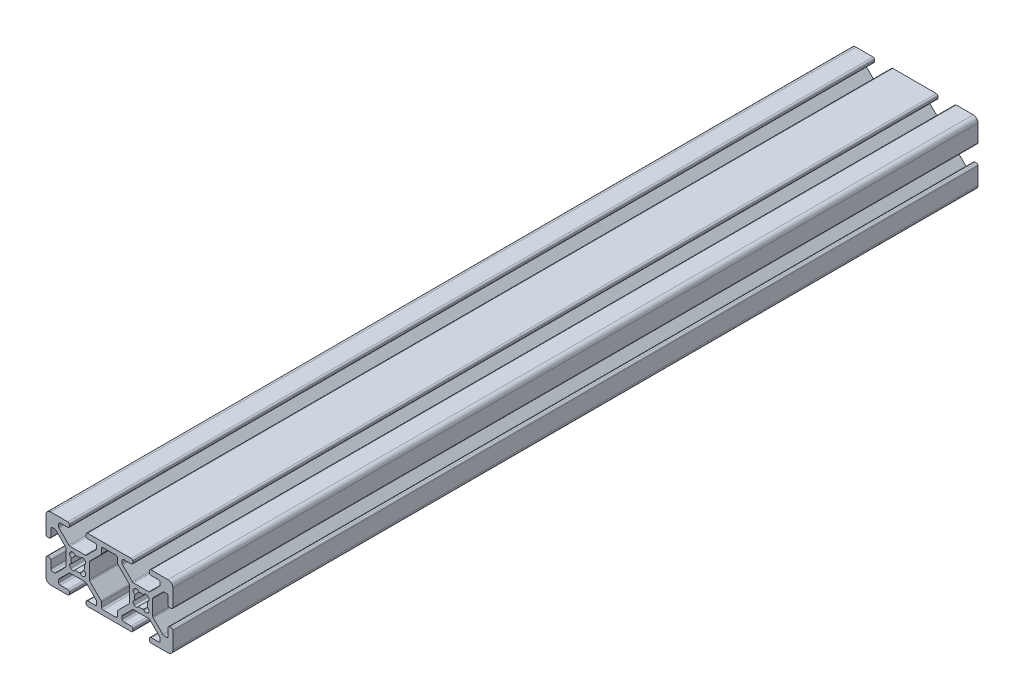
SolidWorks part; units mm, degrees
ref_plane "Front Plane" through (0, 0, 0) normal (0, 0, 1) x (1, 0, 0)
ref_plane "Top Plane" through (0, 0, 0) normal (0, 1, 0) x (1, 0, 0)
ref_plane "Right Plane" through (0, 0, 0) normal (1, 0, 0) x (0, 0, -1)
sketch "Sketch1" plane through (0, 0, 0) normal (0, 0, 1) x (1, 0, 0)
  line L0 (-16.6492, -61.9845) -> (-16.8288, -61.8049)
  line L1 (-16.8288, -57.5551) -> (-16.6492, -57.3755)
  line L2 (-12.3994, -57.3755) -> (-12.2198, -57.5551)
  line L3 (-12.2198, -61.8049) -> (-12.3994, -61.9845)
  line L4 (-27.0293, -67.672) -> (-27.0293, -66.3248)
  line L5 (-27.1781, -65.9655) -> (-30.7205, -62.4231)
  line L6 (-30.8693, -62.0639) -> (-30.8693, -57.2961)
  line L7 (-30.7205, -56.9369) -> (-27.1781, -53.3944)
  line L8 (-27.0293, -53.0352) -> (-27.0293, -51.688)
  line L9 (-26.5213, -51.18) -> (-22.5273, -51.18)
  line L10 (-22.0193, -51.688) -> (-22.0193, -53.0352)
  line L11 (-21.8705, -53.3944) -> (-18.3281, -56.9369)
  line L12 (-18.1793, -57.2961) -> (-18.1793, -62.0639)
  line L13 (-18.3281, -62.4231) -> (-21.8705, -65.9655)
  line L14 (-22.0193, -66.3248) -> (-22.0193, -67.672)
  line L15 (-22.5273, -68.18) -> (-26.5213, -68.18)
  line L16 (-36.6492, -61.9845) -> (-36.8288, -61.8049)
  line L17 (-36.8288, -57.5551) -> (-36.6492, -57.3755)
  line L18 (-32.3994, -57.3755) -> (-32.2198, -57.5551)
  line L19 (-32.2198, -61.8049) -> (-32.3994, -61.9845)
  line L20 (-36.9082, -63.335) -> (-32.1404, -63.335)
  line L21 (-31.7812, -63.4838) -> (-28.6781, -66.5869)
  line L22 (-28.5293, -66.9461) -> (-28.5293, -67.672)
  line L23 (-29.0373, -68.18) -> (-31.3863, -68.18)
  line L24 (-31.8943, -68.688) -> (-31.8943, -69.172)
  line L25 (-31.3863, -69.68) -> (-17.6623, -69.68)
  line L26 (-17.1543, -69.172) -> (-17.1543, -68.688)
  line L27 (-17.6623, -68.18) -> (-20.0113, -68.18)
  line L28 (-20.5193, -67.672) -> (-20.5193, -66.9461)
  line L29 (-20.3705, -66.5869) -> (-17.2674, -63.4838)
  line L30 (-16.9082, -63.335) -> (-12.1404, -63.335)
  line L31 (-11.7812, -63.4838) -> (-8.6781, -66.5869)
  line L32 (-8.5293, -66.9461) -> (-8.5293, -67.672)
  line L33 (-9.0373, -68.18) -> (-11.3863, -68.18)
  line L34 (-11.8943, -68.688) -> (-11.8943, -69.172)
  line L35 (-11.3863, -69.68) -> (-6.0243, -69.68)
  line L36 (-4.5243, -68.18) -> (-4.5243, -62.818)
  line L37 (-5.0323, -62.31) -> (-5.5163, -62.31)
  line L38 (-6.0243, -62.818) -> (-6.0243, -65.167)
  line L39 (-6.5323, -65.675) -> (-7.2582, -65.675)
  line L40 (-7.6174, -65.5262) -> (-10.7205, -62.4231)
  line L41 (-10.8693, -62.0639) -> (-10.8693, -57.2961)
  line L42 (-10.7205, -56.9369) -> (-7.6174, -53.8338)
  line L43 (-7.2582, -53.685) -> (-6.5323, -53.685)
  line L44 (-6.0243, -54.193) -> (-6.0243, -56.542)
  line L45 (-5.5163, -57.05) -> (-5.0323, -57.05)
  line L46 (-4.5243, -56.542) -> (-4.5243, -51.18)
  line L47 (-6.0243, -49.68) -> (-11.3863, -49.68)
  line L48 (-11.8943, -50.188) -> (-11.8943, -50.672)
  line L49 (-11.3863, -51.18) -> (-9.0373, -51.18)
  line L50 (-8.5293, -51.688) -> (-8.5293, -52.4139)
  line L51 (-8.6781, -52.7731) -> (-11.7812, -55.8762)
  line L52 (-12.1404, -56.025) -> (-16.9082, -56.025)
  line L53 (-17.2674, -55.8762) -> (-20.3705, -52.7731)
  line L54 (-20.5193, -52.4139) -> (-20.5193, -51.688)
  line L55 (-20.0113, -51.18) -> (-17.6623, -51.18)
  line L56 (-17.1543, -50.672) -> (-17.1543, -50.188)
  line L57 (-17.6623, -49.68) -> (-31.3863, -49.68)
  line L58 (-31.8943, -50.188) -> (-31.8943, -50.672)
  line L59 (-31.3863, -51.18) -> (-29.0373, -51.18)
  line L60 (-28.5293, -51.688) -> (-28.5293, -52.4139)
  line L61 (-28.6781, -52.7731) -> (-31.7812, -55.8762)
  line L62 (-32.1404, -56.025) -> (-36.9082, -56.025)
  line L63 (-37.2674, -55.8762) -> (-40.3705, -52.7731)
  line L64 (-40.5193, -52.4139) -> (-40.5193, -51.688)
  line L65 (-40.0113, -51.18) -> (-37.6623, -51.18)
  line L66 (-37.1543, -50.672) -> (-37.1543, -50.188)
  line L67 (-37.6623, -49.68) -> (-43.0243, -49.68)
  line L68 (-44.5243, -51.18) -> (-44.5243, -56.542)
  line L69 (-44.0163, -57.05) -> (-43.5323, -57.05)
  line L70 (-43.0243, -56.542) -> (-43.0243, -54.193)
  line L71 (-42.5163, -53.685) -> (-41.7904, -53.685)
  line L72 (-41.4312, -53.8338) -> (-38.3281, -56.9369)
  line L73 (-38.1793, -57.2961) -> (-38.1793, -62.0639)
  line L74 (-38.3281, -62.4231) -> (-41.4312, -65.5262)
  line L75 (-41.7904, -65.675) -> (-42.5163, -65.675)
  line L76 (-43.0243, -65.167) -> (-43.0243, -62.818)
  line L77 (-43.5323, -62.31) -> (-44.0163, -62.31)
  line L78 (-44.5243, -62.818) -> (-44.5243, -68.18)
  line L79 (-43.0243, -69.68) -> (-37.6623, -69.68)
  line L80 (-37.1543, -69.172) -> (-37.1543, -68.688)
  line L81 (-37.6623, -68.18) -> (-40.0113, -68.18)
  line L82 (-40.5193, -67.672) -> (-40.5193, -66.9461)
  line L83 (-40.3705, -66.5869) -> (-37.2674, -63.4838)
  arc A0 (-16.4594, -60.484) -> (-16.8288, -61.8049) centre (-16.2723, -61.2484) ccw
  arc A1 (-16.4594, -58.876) -> (-16.4594, -60.484) centre (-14.5243, -59.68) ccw
  arc A2 (-16.8288, -57.5551) -> (-16.4594, -58.876) centre (-16.2723, -58.1116) ccw
  arc A3 (-15.3283, -57.7449) -> (-16.6492, -57.3755) centre (-16.0927, -57.932) ccw
  arc A4 (-13.7203, -57.7449) -> (-15.3283, -57.7449) centre (-14.5243, -59.68) ccw
  arc A5 (-12.3994, -57.3755) -> (-13.7203, -57.7449) centre (-12.9559, -57.932) ccw
  arc A6 (-12.5892, -58.876) -> (-12.2198, -57.5551) centre (-12.7763, -58.1116) ccw
  arc A7 (-12.5892, -60.484) -> (-12.5892, -58.876) centre (-14.5243, -59.68) ccw
  arc A8 (-12.2198, -61.8049) -> (-12.5892, -60.484) centre (-12.7763, -61.2484) ccw
  arc A9 (-13.7203, -61.6151) -> (-12.3994, -61.9845) centre (-12.9559, -61.428) ccw
  arc A10 (-15.3283, -61.6151) -> (-13.7203, -61.6151) centre (-14.5243, -59.68) ccw
  arc A11 (-16.6492, -61.9845) -> (-15.3283, -61.6151) centre (-16.0927, -61.428) ccw
  arc A12 (-27.0293, -67.672) -> (-26.5213, -68.18) centre (-26.5213, -67.672) ccw
  arc A13 (-27.0293, -66.3248) -> (-27.1781, -65.9655) centre (-27.5373, -66.3248) ccw
  arc A14 (-30.8693, -62.0639) -> (-30.7205, -62.4231) centre (-30.3613, -62.0639) ccw
  arc A15 (-30.7205, -56.9369) -> (-30.8693, -57.2961) centre (-30.3613, -57.2961) ccw
  arc A16 (-27.1781, -53.3944) -> (-27.0293, -53.0352) centre (-27.5373, -53.0352) ccw
  arc A17 (-26.5213, -51.18) -> (-27.0293, -51.688) centre (-26.5213, -51.688) ccw
  arc A18 (-22.0193, -51.688) -> (-22.5273, -51.18) centre (-22.5273, -51.688) ccw
  arc A19 (-22.0193, -53.0352) -> (-21.8705, -53.3944) centre (-21.5113, -53.0352) ccw
  arc A20 (-18.1793, -57.2961) -> (-18.3281, -56.9369) centre (-18.6873, -57.2961) ccw
  arc A21 (-18.3281, -62.4231) -> (-18.1793, -62.0639) centre (-18.6873, -62.0639) ccw
  arc A22 (-21.8705, -65.9655) -> (-22.0193, -66.3248) centre (-21.5113, -66.3248) ccw
  arc A23 (-22.5273, -68.18) -> (-22.0193, -67.672) centre (-22.5273, -67.672) ccw
  arc A24 (-36.4594, -60.484) -> (-36.8288, -61.8049) centre (-36.2723, -61.2484) ccw
  arc A25 (-36.4594, -58.876) -> (-36.4594, -60.484) centre (-34.5243, -59.68) ccw
  arc A26 (-36.8288, -57.5551) -> (-36.4594, -58.876) centre (-36.2723, -58.1116) ccw
  arc A27 (-35.3283, -57.7449) -> (-36.6492, -57.3755) centre (-36.0927, -57.932) ccw
  arc A28 (-33.7203, -57.7449) -> (-35.3283, -57.7449) centre (-34.5243, -59.68) ccw
  arc A29 (-32.3994, -57.3755) -> (-33.7203, -57.7449) centre (-32.9559, -57.932) ccw
  arc A30 (-32.5892, -58.876) -> (-32.2198, -57.5551) centre (-32.7763, -58.1116) ccw
  arc A31 (-32.5892, -60.484) -> (-32.5892, -58.876) centre (-34.5243, -59.68) ccw
  arc A32 (-32.2198, -61.8049) -> (-32.5892, -60.484) centre (-32.7763, -61.2484) ccw
  arc A33 (-33.7203, -61.6151) -> (-32.3994, -61.9845) centre (-32.9559, -61.428) ccw
  arc A34 (-35.3283, -61.6151) -> (-33.7203, -61.6151) centre (-34.5243, -59.68) ccw
  arc A35 (-36.6492, -61.9845) -> (-35.3283, -61.6151) centre (-36.0927, -61.428) ccw
  arc A36 (-36.9082, -63.335) -> (-37.2674, -63.4838) centre (-36.9082, -63.843) ccw
  arc A37 (-31.7812, -63.4838) -> (-32.1404, -63.335) centre (-32.1404, -63.843) ccw
  arc A38 (-28.5293, -66.9461) -> (-28.6781, -66.5869) centre (-29.0373, -66.9461) ccw
  arc A39 (-29.0373, -68.18) -> (-28.5293, -67.672) centre (-29.0373, -67.672) ccw
  arc A40 (-31.3863, -68.18) -> (-31.8943, -68.688) centre (-31.3863, -68.688) ccw
  arc A41 (-31.8943, -69.172) -> (-31.3863, -69.68) centre (-31.3863, -69.172) ccw
  arc A42 (-17.6623, -69.68) -> (-17.1543, -69.172) centre (-17.6623, -69.172) ccw
  arc A43 (-17.1543, -68.688) -> (-17.6623, -68.18) centre (-17.6623, -68.688) ccw
  arc A44 (-20.5193, -67.672) -> (-20.0113, -68.18) centre (-20.0113, -67.672) ccw
  arc A45 (-20.3705, -66.5869) -> (-20.5193, -66.9461) centre (-20.0113, -66.9461) ccw
  arc A46 (-16.9082, -63.335) -> (-17.2674, -63.4838) centre (-16.9082, -63.843) ccw
  arc A47 (-11.7812, -63.4838) -> (-12.1404, -63.335) centre (-12.1404, -63.843) ccw
  arc A48 (-8.5293, -66.9461) -> (-8.6781, -66.5869) centre (-9.0373, -66.9461) ccw
  arc A49 (-9.0373, -68.18) -> (-8.5293, -67.672) centre (-9.0373, -67.672) ccw
  arc A50 (-11.3863, -68.18) -> (-11.8943, -68.688) centre (-11.3863, -68.688) ccw
  arc A51 (-11.8943, -69.172) -> (-11.3863, -69.68) centre (-11.3863, -69.172) ccw
  arc A52 (-6.0243, -69.68) -> (-4.5243, -68.18) centre (-6.0243, -68.18) ccw
  arc A53 (-4.5243, -62.818) -> (-5.0323, -62.31) centre (-5.0323, -62.818) ccw
  arc A54 (-5.5163, -62.31) -> (-6.0243, -62.818) centre (-5.5163, -62.818) ccw
  arc A55 (-6.5323, -65.675) -> (-6.0243, -65.167) centre (-6.5323, -65.167) ccw
  arc A56 (-7.6174, -65.5262) -> (-7.2582, -65.675) centre (-7.2582, -65.167) ccw
  arc A57 (-10.8693, -62.0639) -> (-10.7205, -62.4231) centre (-10.3613, -62.0639) ccw
  arc A58 (-10.7205, -56.9369) -> (-10.8693, -57.2961) centre (-10.3613, -57.2961) ccw
  arc A59 (-7.2582, -53.685) -> (-7.6174, -53.8338) centre (-7.2582, -54.193) ccw
  arc A60 (-6.0243, -54.193) -> (-6.5323, -53.685) centre (-6.5323, -54.193) ccw
  arc A61 (-6.0243, -56.542) -> (-5.5163, -57.05) centre (-5.5163, -56.542) ccw
  arc A62 (-5.0323, -57.05) -> (-4.5243, -56.542) centre (-5.0323, -56.542) ccw
  arc A63 (-4.5243, -51.18) -> (-6.0243, -49.68) centre (-6.0243, -51.18) ccw
  arc A64 (-11.3863, -49.68) -> (-11.8943, -50.188) centre (-11.3863, -50.188) ccw
  arc A65 (-11.8943, -50.672) -> (-11.3863, -51.18) centre (-11.3863, -50.672) ccw
  arc A66 (-8.5293, -51.688) -> (-9.0373, -51.18) centre (-9.0373, -51.688) ccw
  arc A67 (-8.6781, -52.7731) -> (-8.5293, -52.4139) centre (-9.0373, -52.4139) ccw
  arc A68 (-12.1404, -56.025) -> (-11.7812, -55.8762) centre (-12.1404, -55.517) ccw
  arc A69 (-17.2674, -55.8762) -> (-16.9082, -56.025) centre (-16.9082, -55.517) ccw
  arc A70 (-20.5193, -52.4139) -> (-20.3705, -52.7731) centre (-20.0113, -52.4139) ccw
  arc A71 (-20.0113, -51.18) -> (-20.5193, -51.688) centre (-20.0113, -51.688) ccw
  arc A72 (-17.6623, -51.18) -> (-17.1543, -50.672) centre (-17.6623, -50.672) ccw
  arc A73 (-17.1543, -50.188) -> (-17.6623, -49.68) centre (-17.6623, -50.188) ccw
  arc A74 (-31.3863, -49.68) -> (-31.8943, -50.188) centre (-31.3863, -50.188) ccw
  arc A75 (-31.8943, -50.672) -> (-31.3863, -51.18) centre (-31.3863, -50.672) ccw
  arc A76 (-28.5293, -51.688) -> (-29.0373, -51.18) centre (-29.0373, -51.688) ccw
  arc A77 (-28.6781, -52.7731) -> (-28.5293, -52.4139) centre (-29.0373, -52.4139) ccw
  arc A78 (-32.1404, -56.025) -> (-31.7812, -55.8762) centre (-32.1404, -55.517) ccw
  arc A79 (-37.2674, -55.8762) -> (-36.9082, -56.025) centre (-36.9082, -55.517) ccw
  arc A80 (-40.5193, -52.4139) -> (-40.3705, -52.7731) centre (-40.0113, -52.4139) ccw
  arc A81 (-40.0113, -51.18) -> (-40.5193, -51.688) centre (-40.0113, -51.688) ccw
  arc A82 (-37.6623, -51.18) -> (-37.1543, -50.672) centre (-37.6623, -50.672) ccw
  arc A83 (-37.1543, -50.188) -> (-37.6623, -49.68) centre (-37.6623, -50.188) ccw
  arc A84 (-43.0243, -49.68) -> (-44.5243, -51.18) centre (-43.0243, -51.18) ccw
  arc A85 (-44.5243, -56.542) -> (-44.0163, -57.05) centre (-44.0163, -56.542) ccw
  arc A86 (-43.5323, -57.05) -> (-43.0243, -56.542) centre (-43.5323, -56.542) ccw
  arc A87 (-42.5163, -53.685) -> (-43.0243, -54.193) centre (-42.5163, -54.193) ccw
  arc A88 (-41.4312, -53.8338) -> (-41.7904, -53.685) centre (-41.7904, -54.193) ccw
  arc A89 (-38.1793, -57.2961) -> (-38.3281, -56.9369) centre (-38.6873, -57.2961) ccw
  arc A90 (-38.3281, -62.4231) -> (-38.1793, -62.0639) centre (-38.6873, -62.0639) ccw
  arc A91 (-41.7904, -65.675) -> (-41.4312, -65.5262) centre (-41.7904, -65.167) ccw
  arc A92 (-43.0243, -65.167) -> (-42.5163, -65.675) centre (-42.5163, -65.167) ccw
  arc A93 (-43.0243, -62.818) -> (-43.5323, -62.31) centre (-43.5323, -62.818) ccw
  arc A94 (-44.0163, -62.31) -> (-44.5243, -62.818) centre (-44.0163, -62.818) ccw
  arc A95 (-44.5243, -68.18) -> (-43.0243, -69.68) centre (-43.0243, -68.18) ccw
  arc A96 (-37.6623, -69.68) -> (-37.1543, -69.172) centre (-37.6623, -69.172) ccw
  arc A97 (-37.1543, -68.688) -> (-37.6623, -68.18) centre (-37.6623, -68.688) ccw
  arc A98 (-40.5193, -67.672) -> (-40.0113, -68.18) centre (-40.0113, -67.672) ccw
  arc A99 (-40.3705, -66.5869) -> (-40.5193, -66.9461) centre (-40.0113, -66.9461) ccw
extrude "Extrude1" add sketch "Sketch1" along normal blind 254
